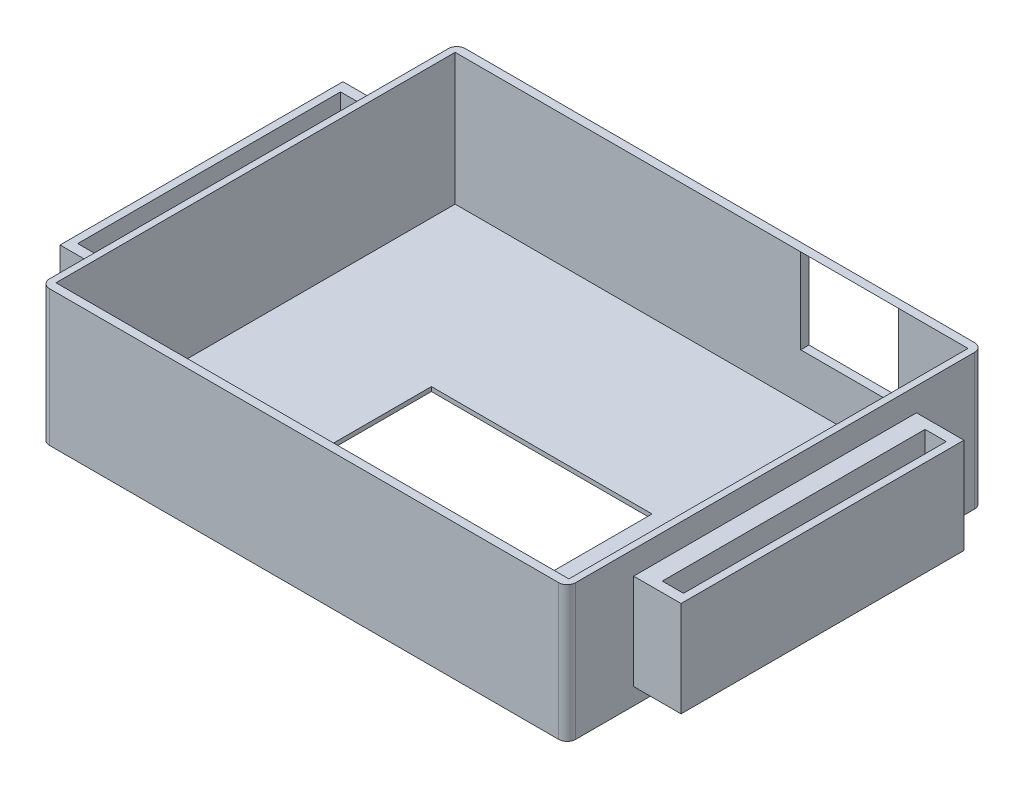
SolidWorks part; units mm, degrees
ref_plane "Front Plane" through (0, 0, 0) normal (0, 0, 1) x (1, 0, 0)
ref_plane "Top Plane" through (0, 0, 0) normal (0, 1, 0) x (1, 0, 0)
ref_plane "Right Plane" through (0, 0, 0) normal (1, 0, 0) x (0, 0, -1)
sketch "Sketch2" plane through (0, 0, 0) normal (0, 1, 0) x (1, 0, 0)
  line L1 (-31, 24.5) -> (31, 24.5)
  line L2 (-31, 24.5) -> (-31, -24.5)
  line L3 (-31, -24.5) -> (31, -24.5)
  line L4 (31, 24.5) -> (31, -24.5)
  line L5 (-31, 24.5) -> (31, -24.5) construction
  line L6 (-31, -24.5) -> (31, 24.5) construction
  point P0 (0, 0)
  dimension "D1" = 49
  dimension "D2" = 62
extrude "Boss-Extrude2" add sketch "Sketch2" along normal blind 16
sketch "Sketch3" plane through (0, 16, 0) normal (0, 1, 0) x (1, 0, 0)
  line L1 (-30.218, 23.518) -> (30.218, 23.518)
  line L2 (-30.218, 23.518) -> (-30.218, -23.518)
  line L3 (-30.218, -23.518) -> (30.218, -23.518)
  line L4 (30.218, 23.518) -> (30.218, -23.518)
  line L5 (-30.218, 23.518) -> (30.218, -23.518) construction
  line L6 (-30.218, -23.518) -> (30.218, 23.518) construction
  point P0 (0, 0)
extrude "Cut-Extrude2" cut sketch "Sketch3" against normal blind 15.492
sketch "Sketch4" plane through (0, 0, 0) normal (0, -1, 0) x (1, 0, 0)
  line L0 (-31, -24.5) -> (-31, 24.5) construction
  line L1 (-13, 22.5) -> (13, 22.5)
  line L2 (-13, 22.5) -> (-13, -3.5)
  line L3 (-13, -3.5) -> (13, -3.5)
  line L4 (13, 22.5) -> (13, -3.5)
  line L5 (-13, 22.5) -> (13, -3.5) construction
  line L6 (-13, -3.5) -> (13, 22.5) construction
  line L7 (-31, 24.5) -> (31, 24.5) construction
  point P0 (0, 9.5)
  dimension "D1" = 18
  dimension "D2" = 26
  dimension "D3" = 26
  dimension "D4" = 2
extrude "Cut-Extrude3" cut sketch "Sketch4" against normal blind 1.014
sketch "Sketch6" plane through (0, 0, -24.5) normal (0, 0, -1) x (-1, 0, 0)
  line L0 (-31, 16) -> (-31, 0) construction
  line L1 (-22, 15.9998) -> (-10.5, 15.9998)
  line L2 (-22, 15.9998) -> (-22, 5.9998)
  line L3 (-22, 5.9998) -> (-10.5, 5.9998)
  line L4 (-10.5, 15.9998) -> (-10.5, 5.9998)
  line L5 (-22, 15.9998) -> (-10.5, 5.9998) construction
  line L6 (-22, 5.9998) -> (-10.5, 15.9998) construction
  line L7 (-31, 16) -> (31, 16) construction
  point P0 (-16.25, 10.9998)
  dimension "D1" = 9
  dimension "D2" = 10
  dimension "D3" = 11.5
  dimension "D4" = 0.0002
extrude "Cut-Extrude4" cut sketch "Sketch6" against normal blind 1.014
fillet "Fillet3" radius 1 4 edges at (31, 8, -24.5) (31, 8, 24.5) (-31, 8, -24.5) (-31, 8, 24.5)
sketch "Sketch8" plane through (-31, 0, 0) normal (-1, 0, 0) x (0, 0, 1)
  line L1 (-16.6654, 13.2467) -> (16.6654, 13.2467)
  line L2 (-16.6654, 13.2467) -> (-16.6654, 1.9806)
  line L3 (-16.6654, 1.9806) -> (16.6654, 1.9806)
  line L4 (16.6654, 13.2467) -> (16.6654, 1.9806)
  line L5 (-16.6654, 13.2467) -> (16.6654, 1.9806) construction
  line L6 (-16.6654, 1.9806) -> (16.6654, 13.2467) construction
  point P0 (0, 7.6137)
  dimension "D1" = 33.3308
  dimension "D2" = 11.2661
extrude "Boss-Extrude3" add sketch "Sketch8" along normal blind 5.586
sketch "Sketch9" plane through (0, 13.2467, 0) normal (0, 1, 0) x (1, 0, 0)
  line L1 (-35.6924, 15.4816) -> (-33.1924, 15.4816)
  line L2 (-35.6924, 15.4816) -> (-35.6924, -15.4816)
  line L3 (-35.6924, -15.4816) -> (-33.1924, -15.4816)
  line L4 (-33.1924, 15.4816) -> (-33.1924, -15.4816)
  line L5 (-35.6924, 15.4816) -> (-33.1924, -15.4816) construction
  line L6 (-35.6924, -15.4816) -> (-33.1924, 15.4816) construction
  point P0 (-34.4424, 0)
  dimension "D1" = 2.5
extrude "Cut-Extrude5" cut sketch "Sketch9" against normal blind 13.714
mirror "Mirror1" about plane through (0, 0, 0) normal (1, 0, 0) of "Boss-Extrude3", "Cut-Extrude5"
